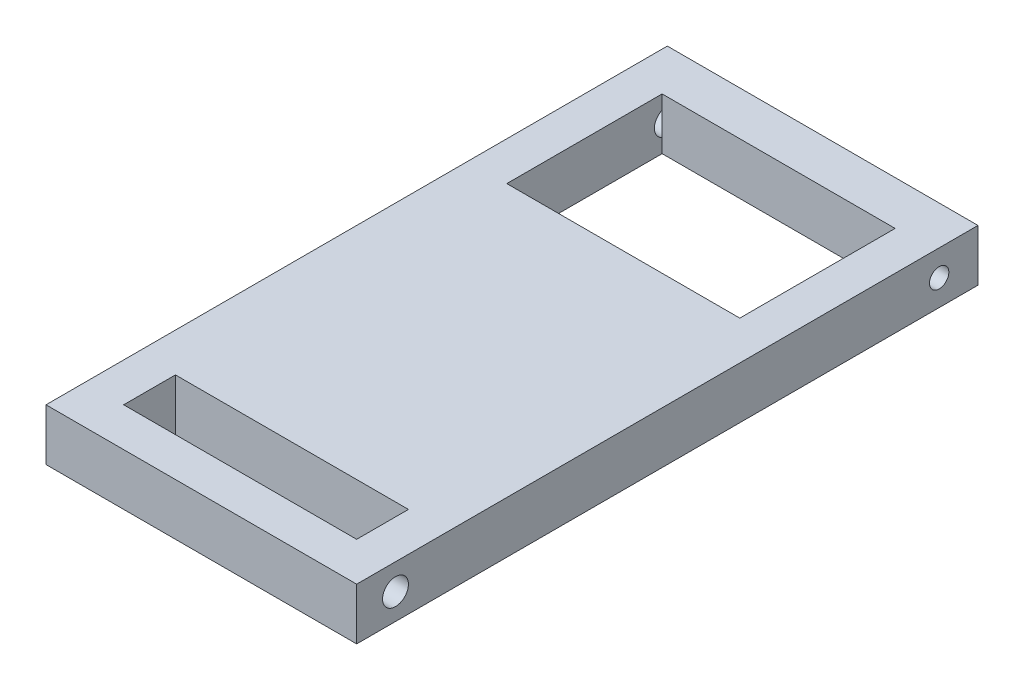
SolidWorks part; units mm, degrees
ref_plane "Front Plane" through (0, 0, 0) normal (0, 0, 1) x (1, 0, 0)
ref_plane "Top Plane" through (0, 0, 0) normal (0, 1, 0) x (1, 0, 0)
ref_plane "Right Plane" through (0, 0, 0) normal (1, 0, 0) x (0, 0, -1)
sketch "Sketch1" plane through (0, 0, 0) normal (0, 1, 0) x (1, 0, 0)
  line L0 (0, 0) -> (152.4, 0)
  line L1 (152.4, 0) -> (152.4, 304.8)
  line L2 (152.4, 304.8) -> (0, 304.8)
  line L3 (0, 304.8) -> (0, 0)
  dimension "D1" = 152.4
  dimension "D2" = 304.8
extrude "Boss-Extrude1" add sketch "Sketch1" along normal blind 25.4
sketch "Sketch2" plane through (152.4, 0, 0) normal (1, 0, 0) x (0, 0, -1)
  line L0 (0, 25.4) -> (0, 0) construction
  line L3 (0, 25.4) -> (304.8, 25.4) construction
  circle A0 centre (19.05, 12.7) radius 6.35
  dimension "D3" = 12.7
  dimension "D1" = 19.05
  dimension "D2" = 12.7
extrude "Cut-Extrude1" cut sketch "Sketch2" against normal blind 19.05 contours A0
sketch "Sketch3" plane through (152.4, 0, 0) normal (1, 0, 0) x (0, 0, -1)
  line L0 (0, 0) -> (304.8, 0) construction
  line L1 (304.8, 25.4) -> (304.8, 0) construction
  circle A0 centre (285.75, 12.7) radius 4.7411
  dimension "D1" = 12.7
  dimension "D2" = 19.05
extrude "Cut-Extrude2" cut sketch "Sketch3" against normal blind 19.05 contours A0
sketch "Sketch8" plane through (0, 0, 0) normal (-1, 0, 0) x (0, 0, 1)
  line L0 (-304.8, 0) -> (0, 0) construction
  line L1 (-304.8, 25.4) -> (-304.8, 0) construction
  line L2 (0, 25.4) -> (0, 0) construction
  circle A0 centre (-285.75, 12.7) radius 6.35
  circle A1 centre (-19.05, 12.7) radius 6.35
  dimension "D5" = 12.7
  dimension "D6" = 12.7
  dimension "D1" = 12.7
  dimension "D2" = 19.05
  dimension "D3" = 12.7
  dimension "D4" = 19.05
extrude "Cut-Extrude3" cut sketch "Sketch8" against normal blind 19.05
sketch "Sketch9" plane through (0, 0, 0) normal (0, 1, 0) x (1, 0, 0)
  line L6 (0, 304.8) -> (0, 0) construction
  line L10 (0, 152.4) -> (152.4, 152.4)
  line L11 (152.4, 0) -> (152.4, 304.8) construction
  line L29 (19.05, 44.45) -> (133.35, 44.45)
  line L50 (152.4, 304.8) -> (0, 304.8) construction
  line L51 (19.05, 19.05) -> (19.05, 44.45)
  line L53 (133.35, 44.45) -> (133.35, 19.05)
  line L54 (133.35, 19.05) -> (19.05, 19.05)
  line L55 (0, 0) -> (152.4, 0) construction
  line L56 (19.05, 283.2001) -> (19.05, 207.0001)
  line L57 (19.05, 207.0001) -> (133.35, 207.0001)
  line L58 (133.35, 207.0001) -> (133.35, 283.2001)
  line L59 (133.35, 283.2001) -> (19.05, 283.2001)
  dimension "D1" = 19.05
  dimension "D2" = 19.05
  dimension "D3" = 19.05
  dimension "D4" = 76.2
  dimension "D5" = 114.3
  dimension "D6" = 25.4
  dimension "D9" = 21.5999
extrude "Cut-Extrude5" cut sketch "Sketch9" along normal blind 27.94
